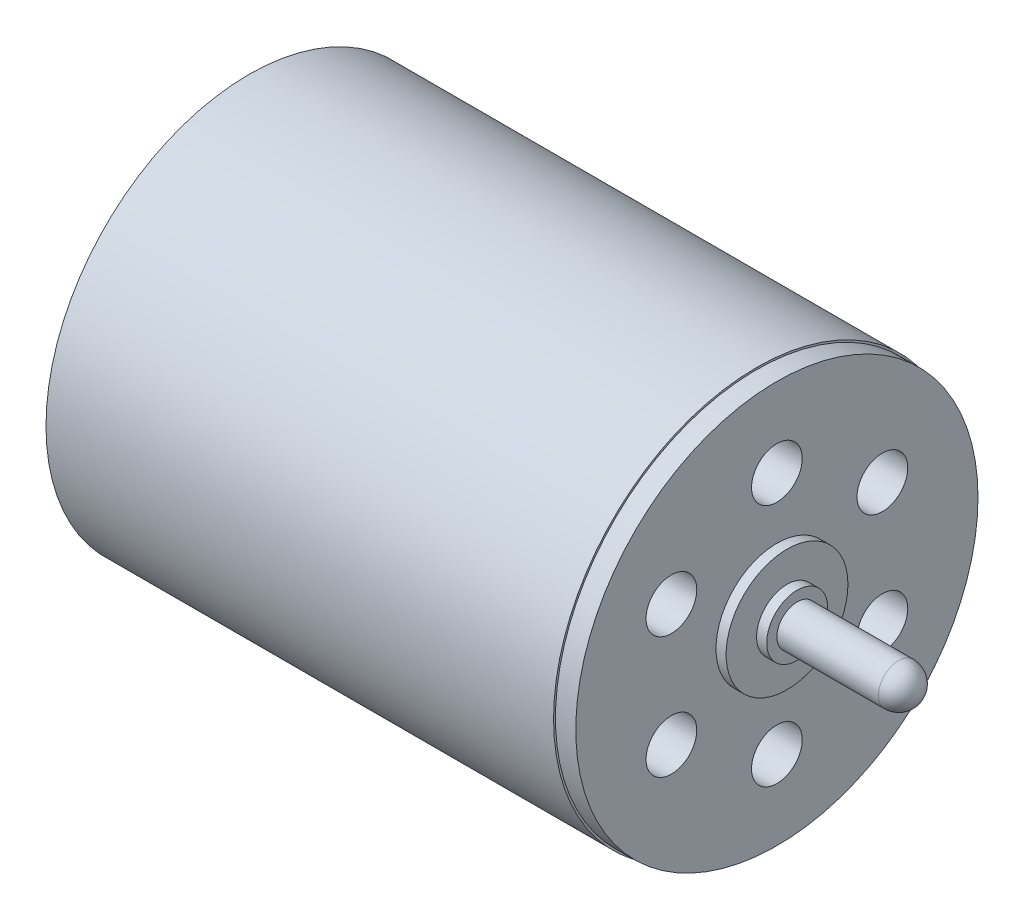
SolidWorks part; units mm, degrees
ref_plane "Alzado" through (0, 0, 0) normal (0, 0, 1) x (1, 0, 0)
ref_plane "Planta" through (0, 0, 0) normal (0, 1, 0) x (1, 0, 0)
ref_plane "Vista lateral" through (0, 0, 0) normal (1, 0, 0) x (0, 0, -1)
sketch "Croquis4" plane through (0, 0, 0) normal (1, 0, 0) x (0, 0, -1)
  circle A0 centre (0, 0) radius 10
  dimension "D1" = 20
extrude "Saliente-Extruir2" add sketch "Croquis4" along normal blind 25
sketch "Croquis5" plane through (25, 0, 0) normal (1, 0, 0) x (0, 0, -1)
  circle A0 centre (0, 0) radius 3
  dimension "D1" = 6
extrude "Saliente-Extruir3" add sketch "Croquis5" along normal blind 1.5
sketch "Croquis6" plane through (26.5, 0, 0) normal (1, 0, 0) x (0, 0, -1)
  circle A0 centre (0, 0) radius 1.5
  dimension "D1" = 3
extrude "Saliente-Extruir4" add sketch "Croquis6" along normal blind 0.5
sketch "Croquis7" plane through (27, 0, 0) normal (1, 0, 0) x (0, 0, -1)
  circle A0 centre (0, 0) radius 1
  dimension "D1" = 2
extrude "Saliente-Extruir5" add sketch "Croquis7" along normal blind 6
fillet "Redondeo1" radius 1 1 edges at (33, 0, -1)
sketch "Croquis10" plane through (25, 0, 0) normal (1, 0, 0) x (0, 0, -1)
  circle A0 centre (0, 0) radius 9.9059
extrude "Saliente-Extruir6" add sketch "Croquis10" along normal blind 1
sketch "Croquis8" plane through (25, 0, 0) normal (1, 0, 0) x (0, 0, -1)
  circle A0 centre (0, 0) radius 6
  circle A1 centre (0, 6) radius 1.25
  circle A2 centre (5.1962, 3) radius 1.25
  circle A3 centre (5.1962, -3) radius 1.25
  circle A4 centre (0, -6) radius 1.25
  circle A5 centre (-5.1962, -3) radius 1.25
  circle A6 centre (-5.1962, 3) radius 1.25
  dimension "D1" = 12
  dimension "D2" = 2.5
  dimension "D3" = 6
extrude "Cortar-Extruir1" cut sketch "Croquis8" against normal blind 6 from surface at 1 contours A0 A6 | A0 A6 | A0 A1 | A0 A1 | A0 A2 | A0 A2 | A0 A3 | A0 A3 | A0 A4 | A0 A4 | A0 A5 | A0 A5
equation "\"6mmmm\"=1.5"
